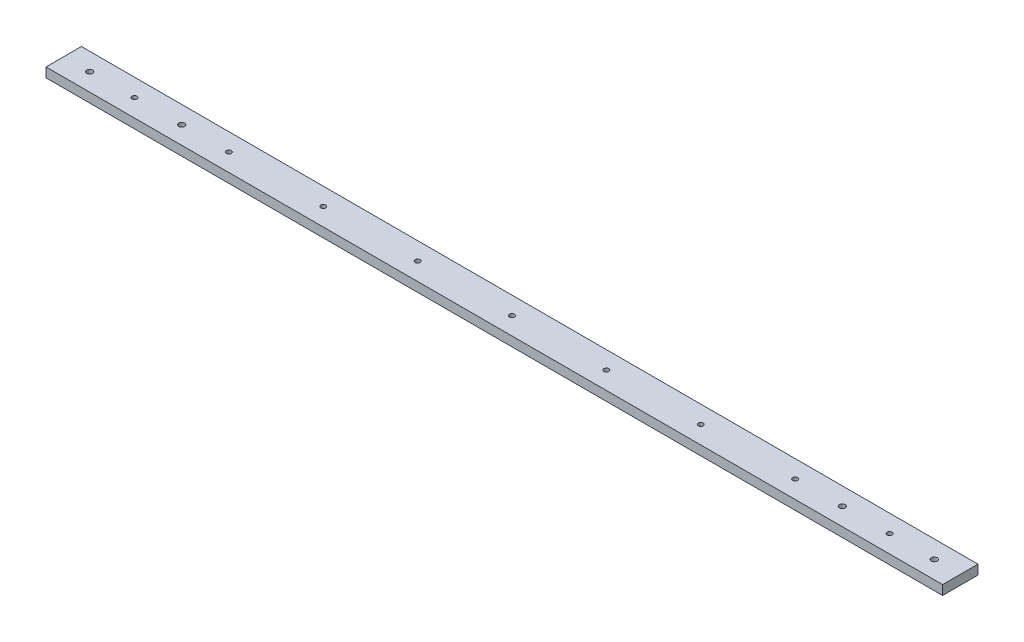
SolidWorks part; units mm, degrees
ref_plane "Front Plane" through (0, 0, 0) normal (0, 0, 1) x (1, 0, 0)
ref_plane "Top Plane" through (0, 0, 0) normal (0, 1, 0) x (1, 0, 0)
ref_plane "Right Plane" through (0, 0, 0) normal (1, 0, 0) x (0, 0, -1)
sketch "Sketch1" plane through (0, 0, 0) normal (0, 1, 0) x (1, 0, 0)
  line L1 (-380, 15) -> (380, 15)
  line L2 (-380, 15) -> (-380, -15)
  line L3 (-380, -15) -> (380, -15)
  line L4 (380, 15) -> (380, -15)
  line L5 (-380, 15) -> (380, -15) construction
  line L6 (-380, -15) -> (380, 15) construction
  point P0 (0, 0)
  dimension "D1" = 760
  dimension "D2" = 30
extrude "Boss-Extrude1" add sketch "Sketch1" along normal blind 8
hole_wizard "M6 Tapped Hole1" positions "Sketch2" profile "Sketch3" tap size "M6" standard "ISO" end condition through all
sketch "Sketch2" plane through (0, 8, 0) normal (0, 1, 0) x (1, 0, 0)
  line L0 (0, 15) -> (0, -15) construction
  line L1 (380, 15) -> (-380, 15) construction
  line L2 (-380, -15) -> (380, -15) construction
  point P0 (-358, 0)
  point P2 (-280, 0)
  point P14 (280, 0)
  point P15 (358, 0)
  dimension "D1" = 78
  dimension "D2" = 280
sketch "Sketch3" plane through (-358, 8, 0) normal (1, 0, 0) x (0, 0, 1)
  line L0 (0, 0) -> (0, 8)
  line L1 (0, 8) -> (2.5, 8)
  line L2 (2.5, 8) -> (2.5, 0)
  line L5 (2.5, 0) -> (0, 0)
  line L11 (0, -6.35) -> (0, 107.95) construction
  dimension "Thru Tap Drill Dia." = 5
  dimension "Thru Tap Drill Depth" = 8
cosmetic thread "Hole Thread1" parameters "D2"=6
cosmetic thread "Hole Thread2" parameters "D2"=6
cosmetic thread "Hole Thread3" parameters "D2"=6
cosmetic thread "Hole Thread4" parameters "D2"=6
hole_wizard "M5 Tapped Hole1" positions "Sketch4" profile "Sketch5" tap size "M5" standard "ISO" end condition through all
sketch "Sketch4" plane through (0, 8, 0) normal (0, 1, 0) x (1, 0, 0)
  point P0 (0, 0)
  point P8 (80, 0)
  point P9 (160, 0)
  point P10 (240, 0)
  point P11 (320, 0)
  point P18 (-80, 0)
  point P19 (-160, 0)
  point P20 (-240, 0)
  point P21 (-320, 0)
  dimension "D1" = 5
  dimension "D2" = 5
sketch "Sketch5" plane through (0, 8, 0) normal (1, 0, 0) x (0, 0, 1)
  line L0 (0, 0) -> (0, 8)
  line L1 (0, 8) -> (2.1, 8)
  line L2 (2.1, 8) -> (2.1, 0)
  line L5 (2.1, 0) -> (0, 0)
  line L11 (0, -6.35) -> (0, 107.95) construction
  dimension "Thru Tap Drill Dia." = 4.2
  dimension "Thru Tap Drill Depth" = 8
cosmetic thread "Hole Thread5" parameters "D2"=5
cosmetic thread "Hole Thread6" parameters "D2"=5
cosmetic thread "Hole Thread7" parameters "D2"=5
cosmetic thread "Hole Thread8" parameters "D2"=5
cosmetic thread "Hole Thread9" parameters "D2"=5
cosmetic thread "Hole Thread10" parameters "D2"=5
cosmetic thread "Hole Thread11" parameters "D2"=5
cosmetic thread "Hole Thread12" parameters "D2"=5
cosmetic thread "Hole Thread13" parameters "D2"=5
